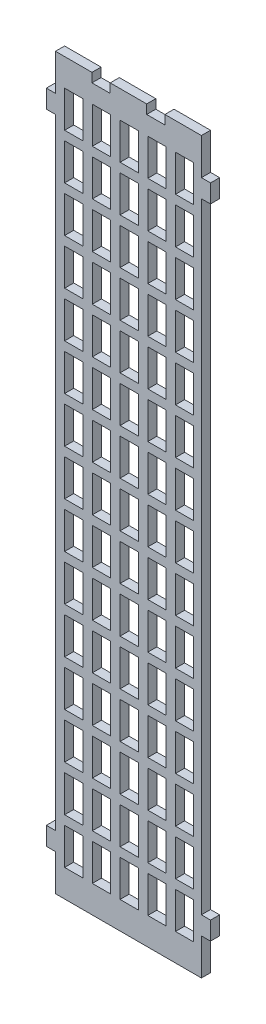
SolidWorks part; units mm, degrees
ref_plane "Front Plane" through (0, 0, 0) normal (0, 0, 1) x (1, 0, 0)
ref_plane "Top Plane" through (0, 0, 0) normal (0, 1, 0) x (1, 0, 0)
ref_plane "Right Plane" through (0, 0, 0) normal (1, 0, 0) x (0, 0, -1)
sketch "Sketch1" plane through (0, 0, 0) normal (0, 0, 1) x (1, 0, 0)
  line L0 (19.05, 0) -> (31.75, 0)
  line L1 (0, 0) -> (12.7, 0)
  line L2 (0, 0) -> (0, -12.7)
  line L3 (0, -254) -> (12.7, -254)
  line L4 (50.8, -19.05) -> (50.8, -234.95)
  line L6 (12.7, 0) -> (12.7, -3.175)
  line L7 (12.7, -3.175) -> (19.05, -3.175)
  line L8 (19.05, 0) -> (19.05, -3.175)
  line L9 (0, -19.05) -> (0, -234.95)
  line L10 (31.75, 0) -> (31.75, -3.175)
  line L11 (31.75, -3.175) -> (38.1, -3.175)
  line L12 (38.1, 0) -> (38.1, -3.175)
  line L13 (50.8, -12.7) -> (53.975, -12.7)
  line L14 (50.8, -241.3) -> (50.8, -254)
  line L15 (50.8, -19.05) -> (53.975, -19.05)
  line L16 (53.975, -12.7) -> (53.975, -19.05)
  line L17 (50.8, -234.95) -> (53.975, -234.95)
  line L18 (38.1, -254) -> (50.8, -254)
  line L19 (50.8, -241.3) -> (53.975, -241.3)
  line L20 (53.975, -234.95) -> (53.975, -241.3)
  line L21 (12.7, -254) -> (38.1, -254)
  line L25 (0, -241.3) -> (0, -254)
  line L29 (0, -241.3) -> (-3.175, -241.3)
  line L30 (38.1, 0) -> (50.8, 0)
  line L31 (0, -234.95) -> (-3.175, -234.95)
  line L32 (-3.175, -241.3) -> (-3.175, -234.95)
  line L33 (0, -19.05) -> (-3.175, -19.05)
  line L34 (50.8, 0) -> (50.8, -12.7)
  line L35 (0, -12.7) -> (-3.175, -12.7)
  line L36 (-3.175, -19.05) -> (-3.175, -12.7)
  dimension "D3" = 12.7
  dimension "D4" = 6.35
  dimension "D5" = 3.175
  dimension "D6" = 6.35
  dimension "D7" = 3.175
  dimension "D8" = 12.7
  dimension "D9" = 12.7
  dimension "D10" = 6.35
  dimension "D11" = 3.175
  dimension "D12" = 3.175
  dimension "D13" = 6.35
  dimension "D14" = 12.7
  dimension "D15" = 50.8
  dimension "D21" = 3.175
  dimension "D22" = 6.35
  dimension "D23" = 12.7
  dimension "D24" = 12.7
  dimension "D25" = 6.35
  dimension "D26" = 3.175
  dimension "D27" = 3.175
  dimension "D29" = 254
extrude "Boss-Extrude1" add sketch "Sketch1" along normal blind 3.175
sketch "Sketch2" plane through (0, 0, 3.175) normal (0, 0, 1) x (1, 0, 0)
  line L0 (0, -19.05) -> (0, -234.95) construction
  line L1 (3.175, -9.525) -> (9.525, -9.525)
  line L2 (3.175, -9.525) -> (3.175, -22.225)
  line L3 (3.175, -22.225) -> (9.525, -22.225)
  line L4 (9.525, -9.525) -> (9.525, -22.225)
  line L5 (3.175, -9.525) -> (9.525, -22.225) construction
  line L6 (3.175, -22.225) -> (9.525, -9.525) construction
  line L7 (12.7, -3.175) -> (19.05, -3.175) construction
  point P0 (6.35, -15.875)
  dimension "D1" = 12.7
  dimension "D2" = 6.35
  dimension "D3" = 3.175
  dimension "D4" = 6.35
extrude "Cut-Extrude1" cut sketch "Sketch2" against normal through all
pattern_linear "LPattern1" count 5 spacing 9.652 along (1, 0, 0) count 15 spacing 15.875 along (0, -1, 0) of "Cut-Extrude1"
